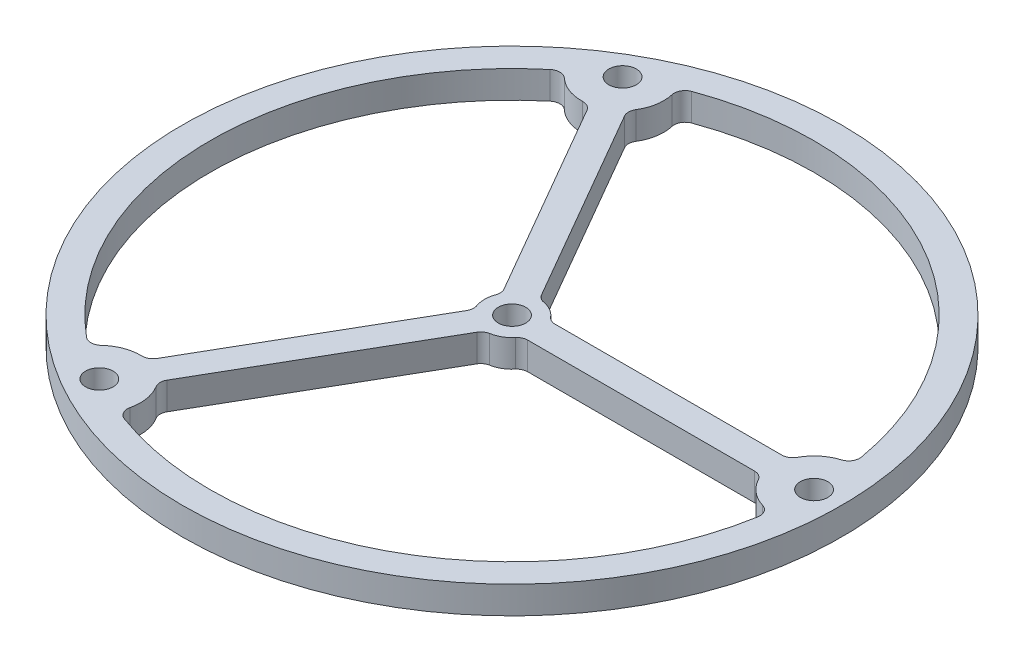
SolidWorks part; units mm, degrees
ref_plane "Front Plane" through (0, 0, 0) normal (0, 0, 1) x (1, 0, 0)
ref_plane "Top Plane" through (0, 0, 0) normal (0, 1, 0) x (1, 0, 0)
ref_plane "Right Plane" through (0, 0, 0) normal (1, 0, 0) x (0, 0, -1)
sketch "Sketch1" plane through (0, 0, 0) normal (0, 1, 0) x (1, 0, 0)
  circle A0 centre (0, 0) radius 76.2
  circle A1 centre (0, 0) radius 3.175
  dimension "D1" = 152.4
  dimension "D2" = 6.35
extrude "Boss-Extrude1" add sketch "Sketch1" along normal blind 3.175
sketch "Sketch2" plane through (0, 3.175, 0) normal (0, 1, 0) x (1, 0, 0)
  circle A0 centre (69.85, 0) radius 3.175
  dimension "D2" = 6.35
  dimension "D1" = 69.85
extrude "Cut-Extrude1" cut sketch "Sketch2" against normal through all
pattern_circular "CirPattern1" count 3 over 360 about axis through (0, 0, 0) along (0, 1, 0) of "Cut-Extrude1"
sketch "Sketch3" plane through (0, 3.175, 0) normal (0, 1, 0) x (1, 0, 0)
  line L0 (-34.925, -60.4919) -> (0, 0) construction
  line L1 (0, -6.35) -> (-27.6852, -54.3022)
  line L2 (-5.4993, -3.175) -> (-33.1845, -51.1272)
  line L3 (0, 0) -> (38.1, -65.9911) construction
  line L4 (0, 0) -> (-76.2, 0) construction
  line L5 (-69.85, 0) -> (-76.2, 0)
  line L6 (34.925, -60.4919) -> (38.1, -65.9911)
  arc A0 (0, -6.35) -> (-5.4993, -3.175) centre (0, 0) ccw
  circle A1 centre (0, 0) radius 3.175
  circle A4 centre (-34.925, -60.4919) radius 3.175
  arc A6 (-26.3706, -64.6809) -> (-27.6852, -54.3022) centre (-34.925, -60.4919) ccw
  arc A8 (-26.3706, -64.6809) -> (34.925, -60.4919) centre (0, 0) ccw
  arc A9 (-69.85, 0) -> (-42.83, -55.178) centre (0, 0) ccw
  arc A10 (-33.1845, -51.1272) -> (-42.83, -55.178) centre (-34.925, -60.4919) ccw
  arc A11 (-76.2, 0) -> (38.1, -65.9911) centre (0, 0) ccw
  dimension "D1" = 12.7
  dimension "D2" = 19.05
  dimension "D6" = 69.85
  dimension "D7" = 69.85
  dimension "D8" = 76.2
  dimension "D3" = 3.175
  dimension "D4" = 60
  dimension "D5" = 60
extrude "Boss-Extrude2" add sketch "Sketch3" along normal blind 3.175
pattern_circular "CirPattern2" count 3 over 360 about axis through (0, 0, 0) along (0, 1, 0) of "Boss-Extrude2"
fillet "Fillet1" radius 2.54 18 edges at (0, 4.7625, 6.35) (-5.4993, 4.7625, 3.175) (-33.1845, 4.7625, 51.1272) (-42.83, 4.7625, 55.178) (-26.3706, 4.7625, 64.6809) (-27.6852, 4.7625, 54.3022) (-5.4993, 4.7625, -3.175) (5.4993, 4.7625, -3.175) (5.4993, 4.7625, 3.175) (60.8697, 4.7625, 3.175) (69.2006, 4.7625, 9.5028) (-26.3706, 4.7625, -64.6809) (69.2006, 4.7625, -9.5028) (60.8697, 4.7625, -3.175) (0, 4.7625, -6.35) (-27.6852, 4.7625, -54.3022) (-42.83, 4.7625, -55.178) (-33.1845, 4.7625, -51.1272)
sketch "Sketch4" plane through (0, 3.175, 0) normal (0, 1, 0) x (1, 0, 0)
  line L0 (-40.896, -39.084) -> (-19.0133, -1.182) construction
  line L1 (-19.0133, 1.182) -> (-40.896, 39.084) construction
  line L2 (-6.1544, 4.3098) -> (-32.3618, 49.7024)
  line L3 (-32.3618, -49.7024) -> (-6.1544, -4.3098)
  line L4 (-6.1544, 4.3098) -> (-32.3618, 49.7024)
  line L5 (-32.3618, -49.7024) -> (-6.1544, -4.3098)
  arc A0 (-41.5223, 39.2686) -> (-41.5223, -39.2686) centre (0, 0) ccw construction
  arc A1 (-41.5223, -39.2686) -> (-41.5223, -39.2686) centre (-41.5223, -39.2686) ccw construction
  arc A2 (-40.896, -39.084) -> (-41.5223, -39.2686) centre (-34.925, -60.4919) ccw construction
  arc A3 (-40.896, -39.084) -> (-40.896, -39.084) centre (-40.896, -39.084) ccw construction
  arc A4 (-19.0133, -1.182) -> (-19.0133, -1.182) centre (-19.0133, -1.182) ccw construction
  arc A5 (-19.0133, 1.182) -> (-19.0133, -1.182) centre (0, 0) ccw construction
  arc A6 (-19.0133, 1.182) -> (-19.0133, 1.182) centre (-19.0133, 1.182) ccw construction
  arc A7 (-40.896, 39.084) -> (-40.896, 39.084) centre (-40.896, 39.084) ccw construction
  arc A8 (-41.5223, 39.2686) -> (-40.896, 39.084) centre (-34.925, 60.4919) ccw construction
  arc A9 (-41.5223, 39.2686) -> (-41.5223, 39.2686) centre (-41.5223, 39.2686) ccw construction
  arc A10 (-32.3618, 49.7024) -> (-34.6381, 50.9712) centre (-34.5615, 48.4324) ccw
  arc A11 (-41.416, 53.521) -> (-34.6381, 50.9712) centre (-34.925, 60.4919) ccw
  arc A12 (-41.416, 53.521) -> (-44.7751, 53.6117) centre (-43.1469, 51.6622) ccw
  arc A13 (-44.7751, 53.6117) -> (-44.7751, -53.6117) centre (0, 0) ccw
  arc A14 (-44.7751, -53.6117) -> (-41.416, -53.521) centre (-43.1469, -51.6622) ccw
  arc A15 (-34.6381, -50.9712) -> (-41.416, -53.521) centre (-34.925, -60.4919) ccw
  arc A16 (-34.6381, -50.9712) -> (-32.3618, -49.7024) centre (-34.5615, -48.4324) ccw
  arc A17 (-6.1544, -4.3098) -> (-5.9672, -2.1713) centre (-8.3541, -3.0398) ccw
  arc A18 (-5.9672, 2.1713) -> (-5.9672, -2.1713) centre (0, 0) ccw
  arc A19 (-5.9672, 2.1713) -> (-6.1544, 4.3098) centre (-8.3541, 3.0398) ccw
  arc A20 (-32.3618, 49.7024) -> (-34.6381, 50.9712) centre (-34.5615, 48.4324) ccw
  arc A21 (-41.416, 53.521) -> (-34.6381, 50.9712) centre (-34.925, 60.4919) ccw
  arc A22 (-41.416, 53.521) -> (-44.7751, 53.6117) centre (-43.1469, 51.6622) ccw
  arc A23 (-44.7751, 53.6117) -> (-44.7751, -53.6117) centre (0, 0) ccw
  arc A24 (-44.7751, -53.6117) -> (-41.416, -53.521) centre (-43.1469, -51.6622) ccw
  arc A25 (-34.6381, -50.9712) -> (-41.416, -53.521) centre (-34.925, -60.4919) ccw
  arc A26 (-34.6381, -50.9712) -> (-32.3618, -49.7024) centre (-34.5615, -48.4324) ccw
  arc A27 (-6.1544, -4.3098) -> (-5.9672, -2.1713) centre (-8.3541, -3.0398) ccw
  arc A28 (-5.9672, 2.1713) -> (-5.9672, -2.1713) centre (0, 0) ccw
  arc A29 (-5.9672, 2.1713) -> (-6.1544, 4.3098) centre (-8.3541, 3.0398) ccw
  dimension "D1" = 0
  dimension "D2" = 12.7
extrude "Cut-Extrude2" cut sketch "Sketch4" against normal through all
pattern_circular "CirPattern3" count 3 over 360 about axis through (0, 3.175, 0) along (0, -1, 0) of "Cut-Extrude2"
